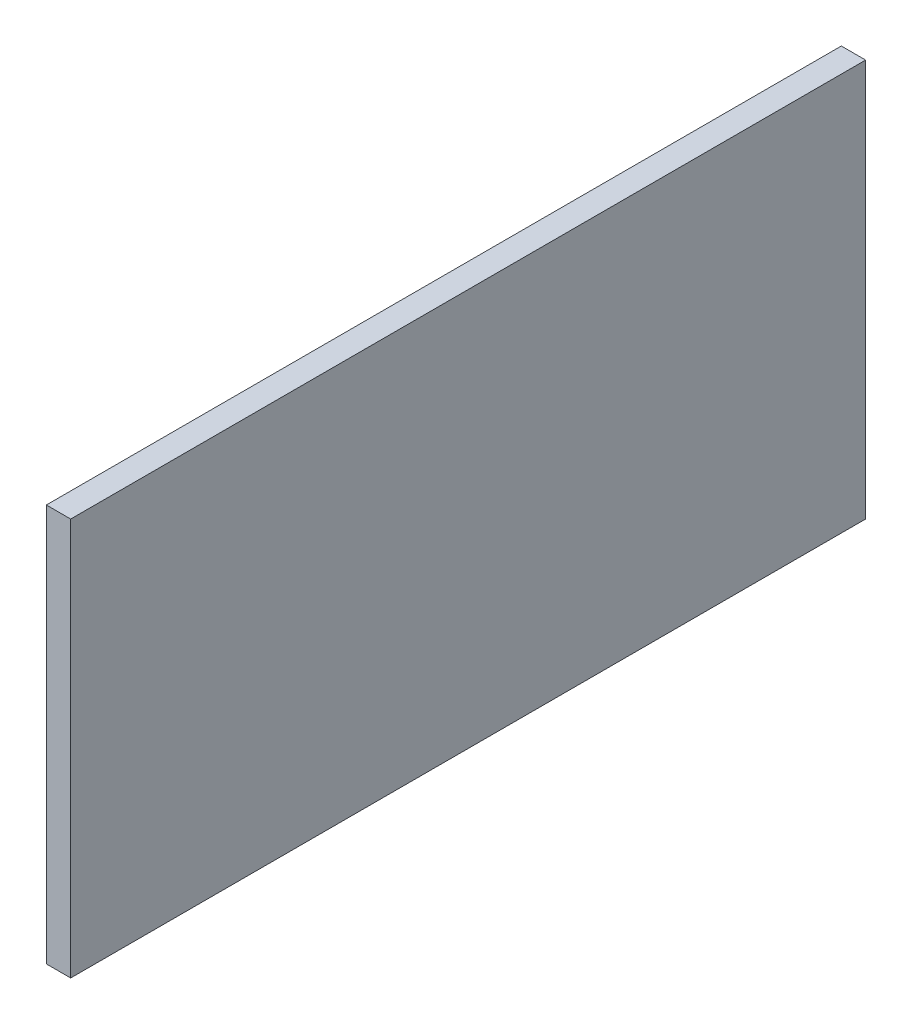
SolidWorks part; units mm, degrees
material "Maple"
ref_plane "Front Plane" through (0, 0, 0) normal (0, 0, 1) x (1, 0, 0)
ref_plane "Top Plane" through (0, 0, 0) normal (0, 1, 0) x (1, 0, 0)
ref_plane "Right Plane" through (0, 0, 0) normal (1, 0, 0) x (0, 0, -1)
sketch "Sketch1" plane through (0, 0, 0) normal (1, 0, 0) x (0, 0, -1)
  line L1 (-200, 0) -> (200, 0)
  line L2 (-200, 0) -> (-200, -200)
  line L3 (-200, -200) -> (200, -200)
  line L4 (200, 0) -> (200, -200)
  point P4 (0, 0)
  dimension "D1" = 400
  dimension "D2" = 200
extrude "Boss-Extrude1" add sketch "Sketch1" along normal blind 12.2428
equation "\"D1@Boss-Extrude1\"=\"Drawer_side_tickness@Drawer Assembly Narrow.Assembly\""
equation "\"D1@Sketch1\"=\"Drawer_length@Drawer Assembly Narrow.Assembly\""
